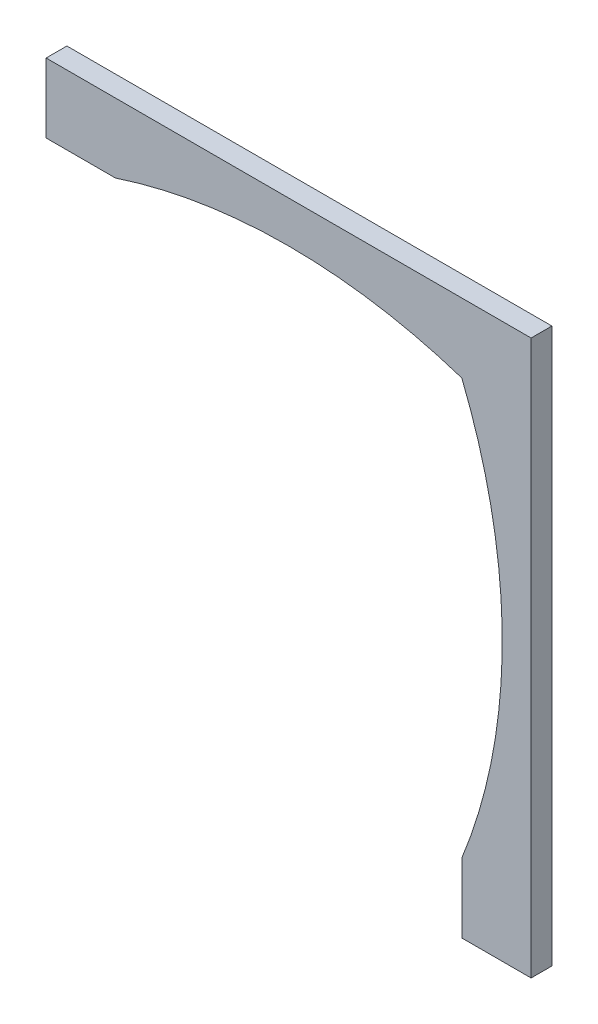
SolidWorks part; units mm, degrees
ref_plane "Front Plane" through (0, 0, 0) normal (0, 0, 1) x (1, 0, 0)
ref_plane "Top Plane" through (0, 0, 0) normal (0, 1, 0) x (1, 0, 0)
ref_plane "Right Plane" through (0, 0, 0) normal (1, 0, 0) x (0, 0, -1)
sketch "Sketch1" plane through (0, 0, 0) normal (0, 0, 1) x (1, 0, 0)
  line L0 (0, 0) -> (-70, 0)
  line L1 (-70, 0) -> (-70, -10)
  line L2 (0, 0) -> (0, -80)
  line L3 (0, -80) -> (-10, -80)
  line L6 (-70, -10) -> (-60, -10)
  line L7 (-10, -80) -> (-10, -70)
  line L8 (-10, -80) -> (-60, -80) construction
  line L9 (-70, -80) -> (0, -80) construction
  line L10 (-60, -10) -> (-60, -70) construction
  arc A5 (-10, -10) -> (-10, -70) centre (-84.162, -40) cw
  arc A6 (-10, -10) -> (-60, -10) centre (-35, -85.9934) ccw
  point P8 (0, 0)
  point P14 (0, 0)
  point P17 (-35, -80)
  point P18 (-60, -40)
  point P19 (-10, -10)
  point P20 (-35, -71.8747)
  point P21 (-20.1011, -35)
  point P23 (0, 0)
  point P24 (-20.1011, -35)
  point P25 (0, 0)
  point P26 (0, 0)
  dimension "D5" = 10
  dimension "D7" = 80
  dimension "D8" = 80
  dimension "D1" = 70
  dimension "D2" = 80
  dimension "D3" = 10
  dimension "D4" = 10
  dimension "D6" = 10
extrude "Boss-Extrude1" add sketch "Sketch1" along normal blind 3
